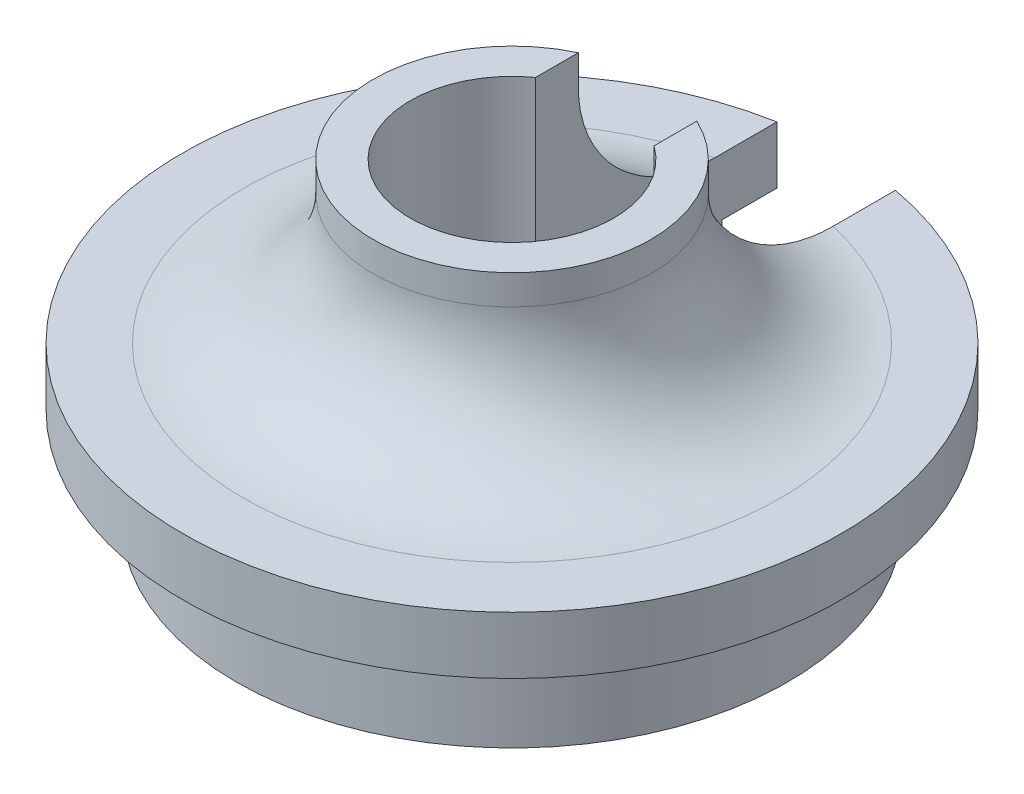
SolidWorks part; units mm, degrees
ref_plane "Front Plane" through (0, 0, 0) normal (0, 0, 1) x (1, 0, 0)
ref_plane "Top Plane" through (0, 0, 0) normal (0, 1, 0) x (1, 0, 0)
ref_plane "Right Plane" through (0, 0, 0) normal (1, 0, 0) x (0, 0, -1)
sketch "Sketch1" plane through (0, 0, 0) normal (1, 0, 0) x (0, 0, -1)
  line L0 (0, 0) -> (2.75, 0)
  line L1 (2.75, 0) -> (2.75, 4.3)
  line L2 (2.75, 4.3) -> (3.75, 4.3)
  line L3 (3.75, 4.3) -> (3.75, 3.5)
  line L4 (7.25, 0) -> (8.9, 0)
  line L5 (8.9, 0) -> (8.9, -1.55)
  line L6 (8.9, -1.55) -> (7.45, -1.55)
  line L7 (7.45, -1.55) -> (7.45, -4.2)
  line L8 (7.45, -4.2) -> (6.65, -4.2)
  line L9 (6.65, -4.2) -> (6.65, -1.55)
  line L10 (6.65, -1.55) -> (0, -1.55)
  line L11 (0, -1.55) -> (0, 0)
  arc A0 (3.75, 3.5) -> (7.25, 0) centre (7.25, 3.5) ccw
  point P5 (0, 0)
  dimension "D8" = 3.5
  dimension "D1" = 8.9
  dimension "D2" = 7.45
  dimension "D3" = 6.65
  dimension "D4" = 3.75
  dimension "D5" = 2.75
  dimension "D6" = 8.5
  dimension "D7" = 4.3
  dimension "D9" = 1.55
revolve "Revolve1" add sketch "Sketch1" angle 360 about L11
sketch "Sketch2" plane through (0, -1.55, 0) normal (0, -1, 0) x (1, 0, 0)
  line L0 (0, 0) -> (0, -8.9) construction
  line L1 (1.6, 0) -> (1.6, -8.9)
  line L2 (-1.6, 0) -> (-1.6, -8.9)
  circle A0 centre (0, 0) radius 8.9 construction
  arc A1 (1.6, 0) -> (-1.6, 0) centre (0, 0) ccw
  arc A2 (-1.6, -8.9) -> (1.6, -8.9) centre (0, -8.9) ccw
  point P6 (0, -4.45)
  dimension "D1" = 1.6
extrude "Cut-Extrude1" cut sketch "Sketch2" against normal through all both and the other way through all
sketch "Sketch3" plane through (0, -1.55, 0) normal (0, -1, 0) x (1, 0, 0)
  line L0 (-1.6, 0) -> (0, 0) construction
  line L1 (0, 0) -> (-4.3301, -2.5) construction
  circle A0 centre (-4.3301, -2.5) radius 1
  circle A1 centre (-4.3301, 2.5) radius 1
  circle A2 centre (0, 5) radius 1
  circle A3 centre (4.3301, 2.5) radius 1
  circle A4 centre (4.3301, -2.5) radius 1
  circle A5 centre (0, -5) radius 1
  point P6 (0, 0)
  point P7 (-2.4711, 7.45)
  point P8 (0, -5.4216)
  point P19 (-4.3301, 4.7086)
  point P20 (6.65, 3.8359)
  point P21 (0, 0)
  dimension "D2" = 2
  dimension "D1" = 30
  dimension "D3" = 5
  dimension "D4" = 6
extrude "Cut-Extrude2" cut sketch "Sketch3" against normal blind 1
